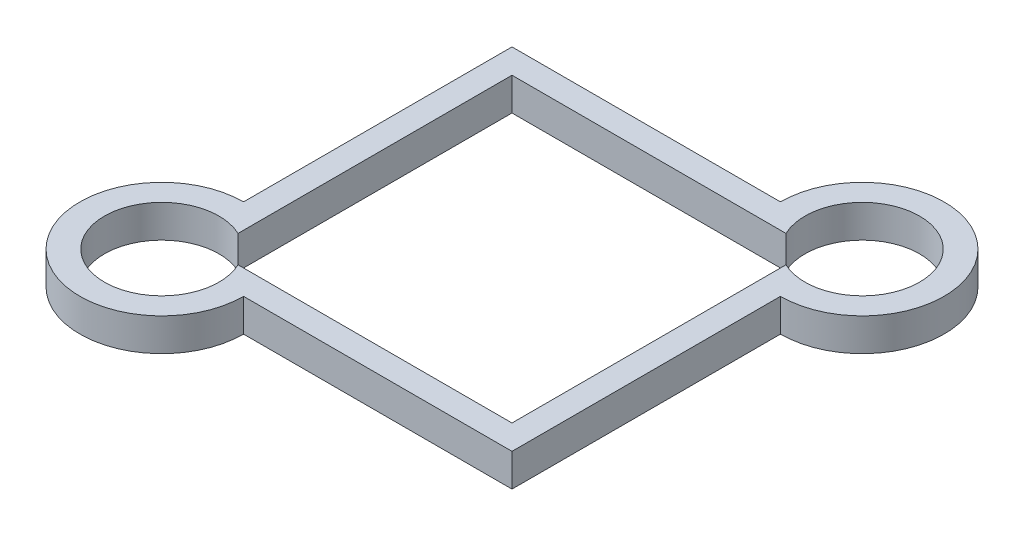
SolidWorks part; units mm, degrees
ref_plane "Front Plane" through (0, 0, 0) normal (0, 0, 1) x (1, 0, 0)
ref_plane "Top Plane" through (0, 0, 0) normal (0, 1, 0) x (1, 0, 0)
ref_plane "Right Plane" through (0, 0, 0) normal (1, 0, 0) x (0, 0, -1)
sketch "Sketch1" plane through (0, 0, 0) normal (0, 1, 0) x (1, 0, 0)
  line L1 (0, 214) -> (0, 50)
  line L2 (50, 0) -> (214, 0)
  line L3 (214, 0) -> (214, 164)
  line L4 (15, 199) -> (15, 31.6228)
  line L5 (31.6228, 15) -> (199, 15)
  line L6 (199, 15) -> (199, 182.3772)
  line L7 (182.3772, 199) -> (15, 199)
  line L8 (0, 0) -> (214, 0) construction
  line L9 (0, 214) -> (0, 0) construction
  line L10 (15, 199) -> (15, 15) construction
  line L11 (15, 15) -> (199, 15) construction
  line L12 (164, 214) -> (0, 214)
  line L13 (214, 214) -> (0, 214) construction
  line L14 (214, 0) -> (214, 214) construction
  line L15 (199, 15) -> (199, 199) construction
  line L16 (199, 199) -> (15, 199) construction
  arc A0 (0, 50) -> (50, 0) centre (0, 0) ccw
  arc A1 (214, 164) -> (164, 214) centre (214, 214) ccw
  arc A2 (15, 31.6228) -> (31.6228, 15) centre (0, 0) ccw
  arc A3 (199, 182.3772) -> (182.3772, 199) centre (214, 214) ccw
  point P8 (0, 0)
  point P13 (0, 0)
  point P16 (0, 0)
  dimension "D1" = 214
  dimension "D2" = 214
  dimension "D3" = 100
  dimension "D4" = 100
  dimension "D5" = 70
  dimension "D6" = 70
  dimension "D7" = 15
  dimension "D8" = 199
extrude "Boss-Extrude1" add sketch "Sketch1" along normal blind 20
